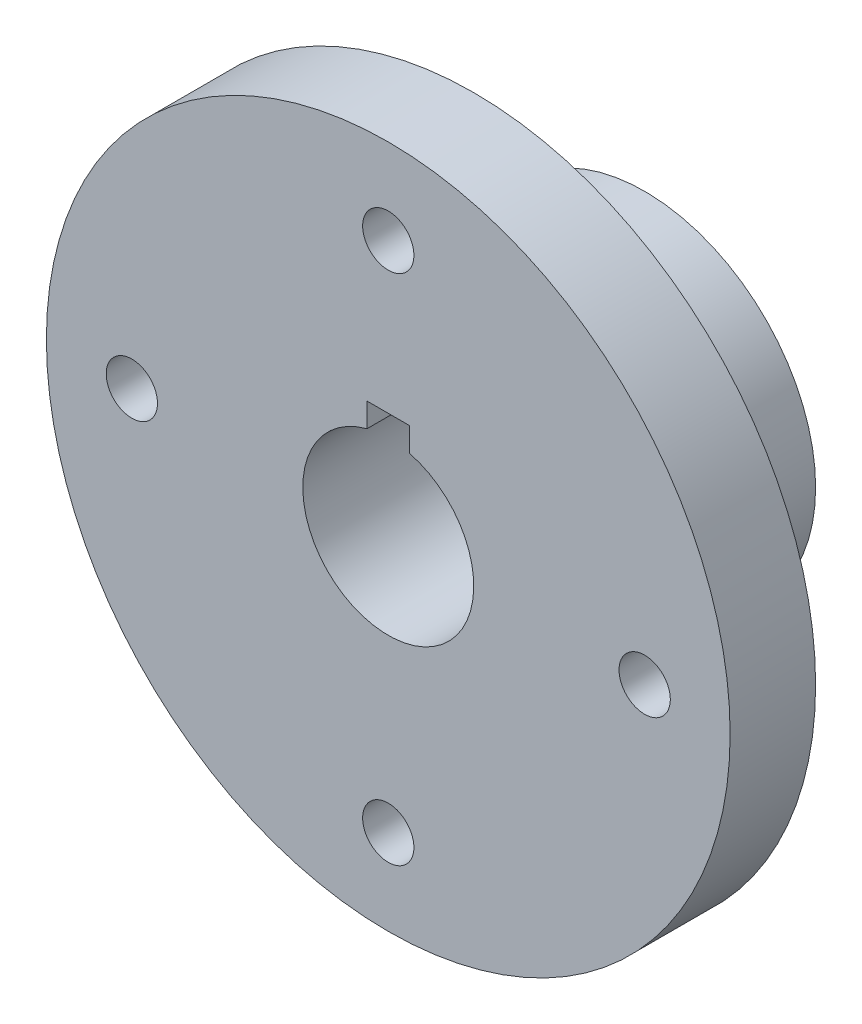
SolidWorks part; units mm, degrees
ref_plane "Front Plane" through (0, 0, 0) normal (0, 0, 1) x (1, 0, 0)
ref_plane "Top Plane" through (0, 0, 0) normal (0, 1, 0) x (1, 0, 0)
ref_plane "Right Plane" through (0, 0, 0) normal (1, 0, 0) x (0, 0, -1)
sketch "Sketch1" plane through (0, 0, 0) normal (0, 0, 1) x (1, 0, 0)
  circle A0 centre (0, 0) radius 200
extrude "Boss-Extrude1" add sketch "Sketch1" along normal blind 50
sketch "Sketch2" plane through (0, 0, 0) normal (0, 0, -1) x (-1, 0, 0)
  circle A0 centre (0, 0) radius 100
extrude "Boss-Extrude2" add sketch "Sketch2" along normal blind 100
sketch "Sketch3" plane through (0, 0, 50) normal (0, 0, 1) x (1, 0, 0)
  circle A0 centre (0, 150) radius 15
  circle A1 centre (150, 0) radius 15
  circle A2 centre (0, -150) radius 15
  circle A3 centre (-150, 0) radius 15
  point P12 (0, 0)
  dimension "D1" = 150
  dimension "D2" = 4
extrude "Cut-Extrude1" cut sketch "Sketch3" against normal through all
sketch "Sketch4" plane through (0, 0, 50) normal (0, 0, 1) x (1, 0, 0)
  circle A0 centre (0, 0) radius 50
extrude "Cut-Extrude2" cut sketch "Sketch4" against normal through all
sketch "Sketch5" plane through (0, 0, 50) normal (0, 0, 1) x (1, 0, 0)
  line L1 (-12.5, 62.5) -> (12.5, 62.5)
  line L2 (-12.5, 62.5) -> (-12.5, 37.5)
  line L3 (-12.5, 37.5) -> (12.5, 37.5)
  line L4 (12.5, 62.5) -> (12.5, 37.5)
  line L5 (-12.5, 62.5) -> (12.5, 37.5) construction
  line L6 (-12.5, 37.5) -> (12.5, 62.5) construction
  circle A0 centre (0, 0) radius 50 construction
  point P0 (0, 50)
extrude "Cut-Extrude3" cut sketch "Sketch5" against normal through all
